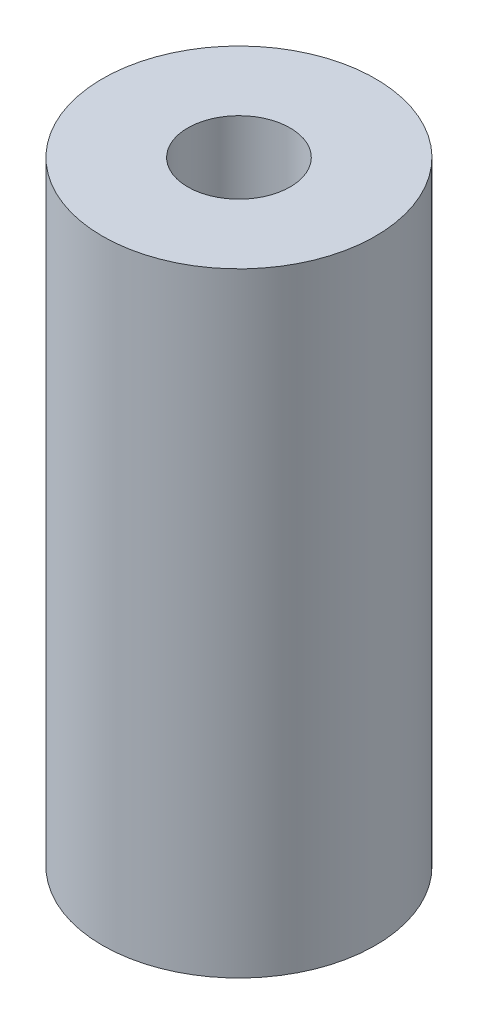
SolidWorks part; units mm, degrees
material "1060 Alloy"
ref_plane "Front Plane" through (0, 0, 0) normal (0, 0, 1) x (1, 0, 0)
ref_plane "Top Plane" through (0, 0, 0) normal (0, 1, 0) x (1, 0, 0)
ref_plane "Right Plane" through (0, 0, 0) normal (1, 0, 0) x (0, 0, -1)
sketch "Sketch1" plane through (0, 0, 0) normal (0, 1, 0) x (1, 0, 0)
  circle A0 centre (0, 0) radius 1.5
  circle A1 centre (0, 0) radius 4
  dimension "D1" = 3
  dimension "D2" = 8
extrude "Boss-Extrude1" add sketch "Sketch1" along normal blind 18
